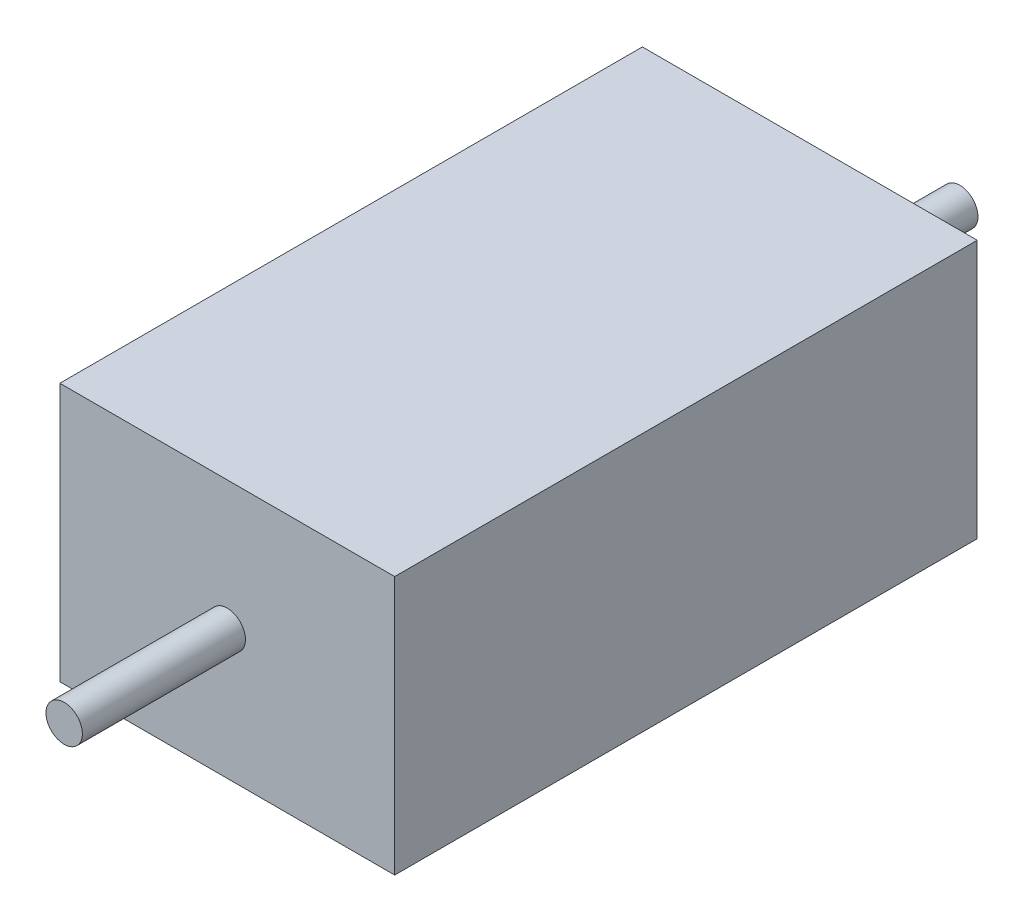
SolidWorks part; units mm, degrees
ref_plane "Front Plane" through (0, 0, 0) normal (0, 0, 1) x (1, 0, 0)
ref_plane "Top Plane" through (0, 0, 0) normal (0, 1, 0) x (1, 0, 0)
ref_plane "Right Plane" through (0, 0, 0) normal (1, 0, 0) x (0, 0, -1)
sketch "Sketch1" plane through (0, 0, 0) normal (0, 0, 1) x (1, 0, 0)
  line L1 (29.7002, -258.8435) -> (259.624, -258.8435)
  line L2 (29.7002, -258.8435) -> (29.7002, -81.3287)
  line L3 (29.7002, -81.3287) -> (259.624, -81.3287)
  line L4 (259.624, -258.8435) -> (259.624, -81.3287)
  line L5 (29.7002, -258.8435) -> (259.624, -81.3287) construction
  line L6 (29.7002, -81.3287) -> (259.624, -258.8435) construction
  point P0 (144.6621, -170.0861)
extrude "Boss-Extrude1" add sketch "Sketch1" along normal blind 400
sketch "Sketch2" plane through (0, 0, 400) normal (0, 0, 1) x (1, 0, 0)
  circle A0 centre (144.6621, -170.0861) radius 12.5
  dimension "D1" = 25
extrude "Boss-Extrude2" add sketch "Sketch2" along normal blind 112 and the other way blind 503
